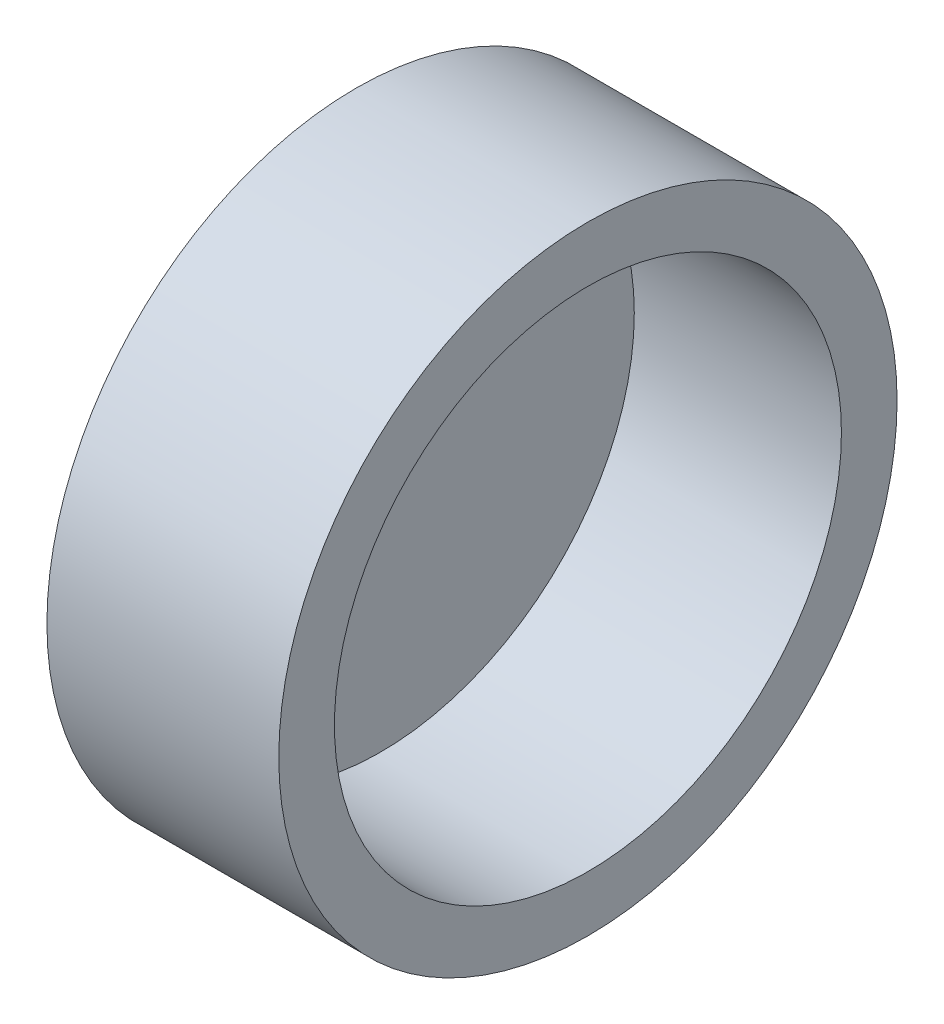
SolidWorks part; units mm, degrees
other "Available_Duct_Packaging"
other "Brake_Rotor_Volume"
ref_plane "Front Plane" through (0, 0, 0) normal (0, 0, 1) x (1, 0, 0)
ref_plane "Top Plane" through (0, 0, 0) normal (0, 1, 0) x (1, 0, 0)
ref_plane "Right Plane" through (0, 0, 0) normal (1, 0, 0) x (0, 0, -1)
other "Configuration Table"
sketch "Sketch1" plane through (0, 0, 0) normal (1, 0, 0) x (0, 0, -1)
  circle A0 centre (0, 0) radius 164
extrude "Rotor_Volume_Extrude" add sketch "Sketch1" along normal mid plane 32 separate body
sketch "Sketch2" plane through (0, 0, 0) normal (1, 0, 0) x (0, 0, -1)
  circle A0 centre (0, 0) radius 164
  circle A1 centre (0, 0) radius 200
extrude "Duct_Packaging_Extrude" add sketch "Sketch2" along normal blind 150 separate body
